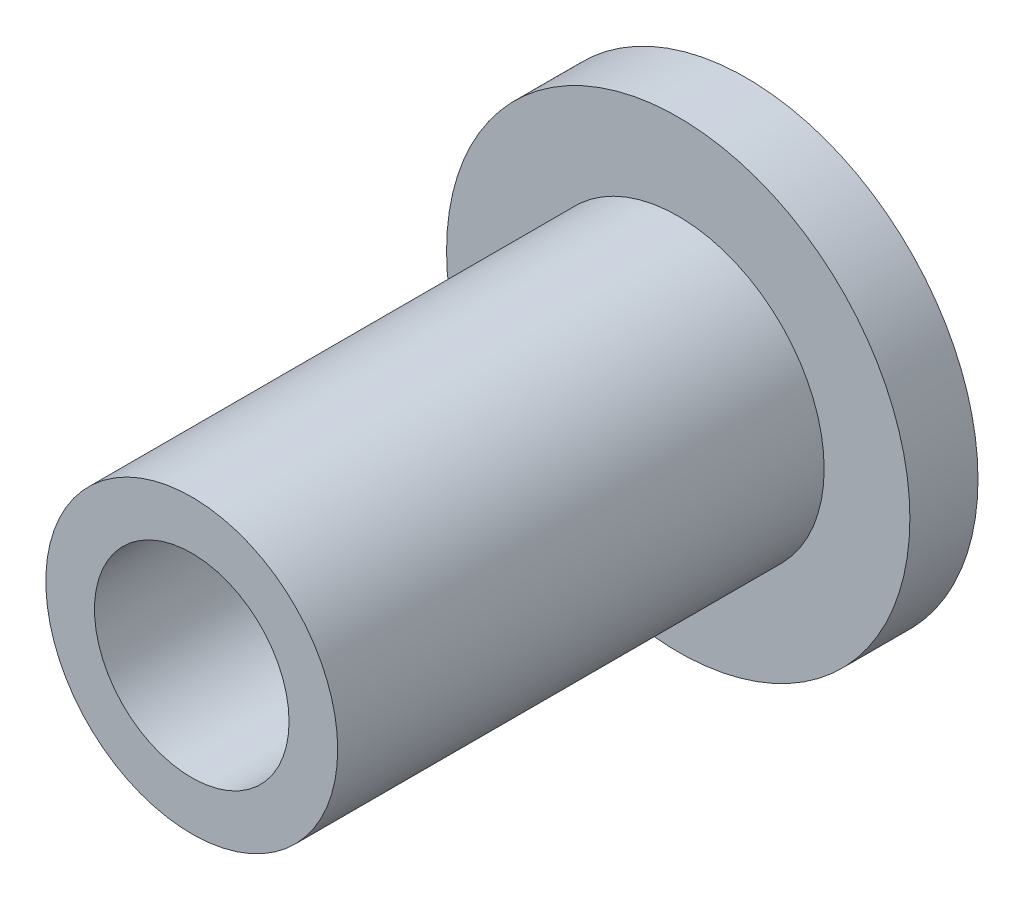
SolidWorks part; units mm, degrees
ref_plane "Front Plane" through (0, 0, 0) normal (1, 0, 0) x (0, 1, 0)
ref_plane "Top Plane" through (0, 0, 0) normal (0, 0, 1) x (0, 1, 0)
ref_plane "Right Plane" through (0, 0, 0) normal (0, 1, 0) x (-1, 0, 0)
sketch "Sketch1" plane through (0, 0, 0) normal (0, 0, 1) x (0, 1, 0)
  circle A0 centre (0, 0) radius 2
  circle A1 centre (0, 0) radius 4.7625
  dimension "D1" = 4
  dimension "D2" = 9.525
extrude "Boss-Extrude1" add sketch "Sketch1" along normal blind 1.4
sketch "Sketch2" plane through (0, 0, 1.4) normal (0, 0, 1) x (1, 0, 0)
  circle A0 centre (0, 0) radius 3
  circle A1 centre (0, 0) radius 2 construction
  circle A2 centre (0, 0) radius 2
  dimension "D1" = 6
extrude "Boss-Extrude2" add sketch "Sketch2" along normal blind 10
